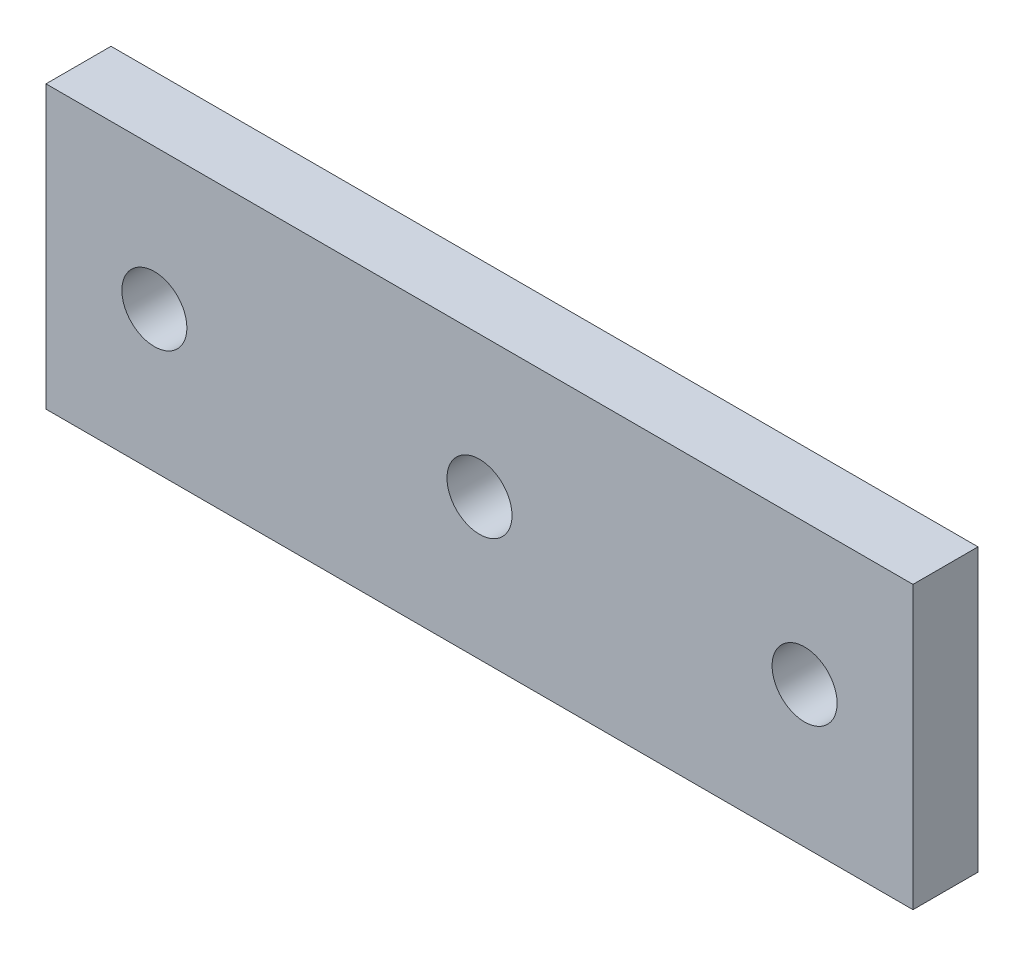
SolidWorks part; units mm, degrees
ref_plane "前基準面" through (0, 0, 0) normal (0, 0, 1) x (1, 0, 0)
ref_plane "上基準面" through (0, 0, 0) normal (0, 1, 0) x (1, 0, 0)
ref_plane "右基準面" through (0, 0, 0) normal (1, 0, 0) x (0, 0, -1)
sketch "草圖1" plane through (0, 0, 0) normal (0, 0, 1) x (1, 0, 0)
  line L0 (0, 0) -> (15, 0) construction
  line L1 (0, 0) -> (-15, 0) construction
  line L3 (-20, -6.5) -> (20, -6.5)
  line L4 (-20, -6.5) -> (-20, 6.5)
  line L5 (-20, 6.5) -> (20, 6.5)
  line L6 (20, -6.5) -> (20, 6.5)
  line L7 (-20, -6.5) -> (20, 6.5) construction
  line L8 (-20, 6.5) -> (20, -6.5) construction
  circle A0 centre (0, 0) radius 1.5
  circle A1 centre (-15, 0) radius 1.5
  circle A2 centre (15, 0) radius 1.5
  dimension "D3" = 3
  dimension "D4" = 3
  dimension "D1" = 40
  dimension "D2" = 13
  dimension "D5" = 15
extrude "填料-伸長1" add sketch "草圖1" along normal blind 3
